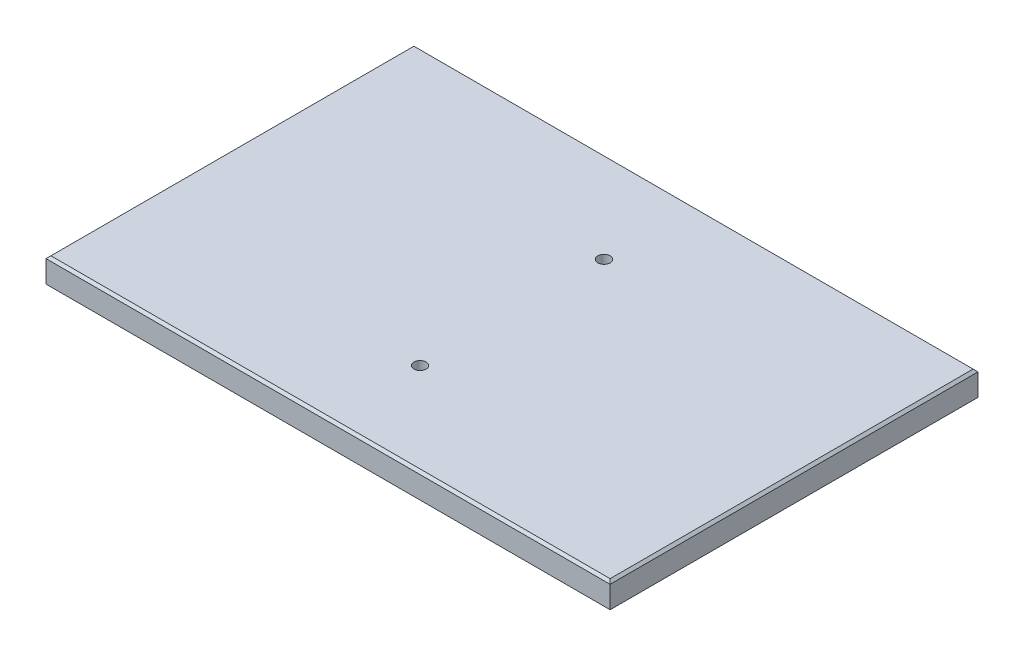
SolidWorks part; units mm, degrees
ref_plane "Спереди" through (0, 0, 0) normal (0, 0, 1) x (1, 0, 0)
ref_plane "Сверху" through (0, 0, 0) normal (0, 1, 0) x (1, 0, 0)
ref_plane "Справа" through (0, 0, 0) normal (1, 0, 0) x (0, 0, -1)
sketch "Эскиз1" plane through (0, 0, 0) normal (0, 1, 0) x (1, 0, 0)
  line L0 (-115, 75) -> (115, -75) construction
  line L1 (115, -75) -> (-115, -75)
  line L2 (115, -75) -> (115, 75)
  line L3 (115, 75) -> (-115, 75)
  line L4 (-115, -75) -> (-115, 75)
  dimension "D1" = 150
  dimension "D2" = 230
  dimension "D3" = 230
  dimension "D4" = 150
extrude "Бобышка-Вытянуть1" add sketch "Эскиз1" against normal blind 10
chamfer "Фаска1" distance 1 angle 45 4 edges at (115, 0, 0) (0, 0, -75) (-115, 0, 0) (0, 0, 75)
hole_wizard "Ø5.0mm Dowel Hole1" positions "Эскиз3" profile "Эскиз2" hole size "Ø5.0" standard "ISO"
sketch "Эскиз3" plane through (0, 0, 0) normal (0, 1, 0) x (-1, 0, 0)
  line L0 (-115, 75) -> (115, 75) construction
  point P0 (0, 37.5)
  point P1 (0, -37.5)
  dimension "D1" = 75
  dimension "D2" = 37.5
sketch "Эскиз2" plane through (0, 0, 37.5) normal (1, 0, 0) x (0, 0, 1)
  line L0 (0, 0) -> (0, 11.5022)
  line L1 (0, 11.5022) -> (2.5, 10)
  line L2 (2.5, 10) -> (2.5, 0)
  line L5 (2.5, 0) -> (0, 0)
  line L10 (0, 11.5022) -> (-2.5, 10) construction
  line L11 (0, -6.35) -> (0, 107.95) construction
  dimension "Hole Dia." = 5
  dimension "Hole Depth" = 10
  dimension "Drill Angle" = 118
ref_plane "SettingPlane" through (0, 0, 0) normal (0, -1, 0) x (-1, 0, 0)
equation "\"Length\"= 150мм"
equation "\"B\"= 230мм"
equation "\"D1@Эскиз1\" = \"Length\""
equation "\"D2@Эскиз3\" = \"D1@Эскиз1\"/4"
equation "\"D1@Эскиз3\" = \"D1@Эскиз1\"/2"
equation "\"D2@Эскиз1\" = \"B\""
